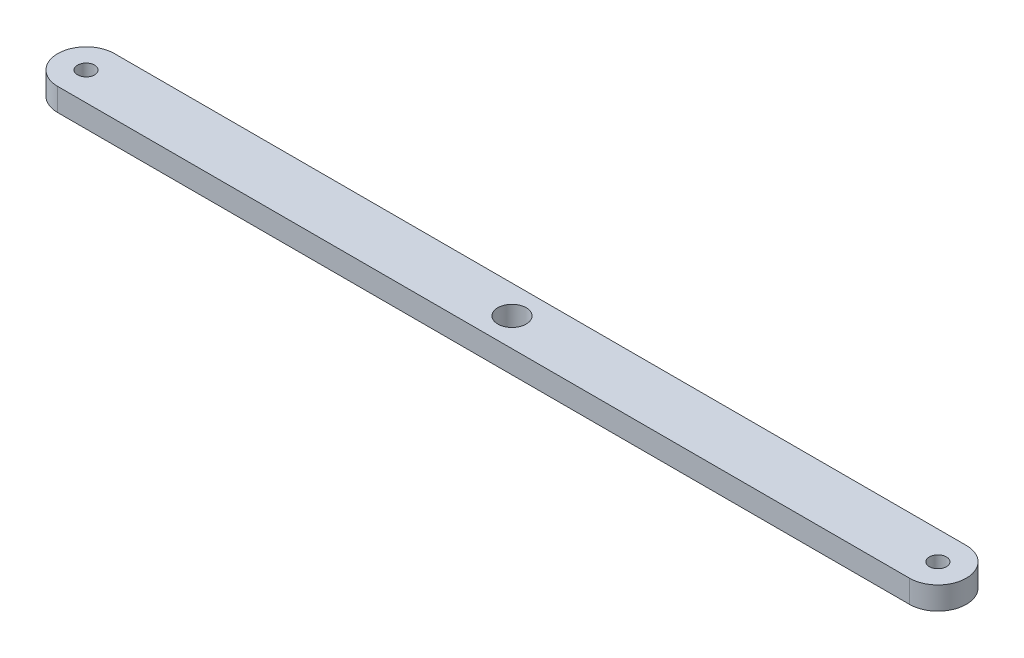
SolidWorks part; units mm, degrees
material "ABS"
ref_plane "Спереди" through (0, 0, 0) normal (0, 0, 1) x (1, 0, 0)
ref_plane "Сверху" through (0, 0, 0) normal (0, 1, 0) x (1, 0, 0)
ref_plane "Справа" through (0, 0, 0) normal (1, 0, 0) x (0, 0, -1)
sketch "Эскиз1" plane through (0, 0, 0) normal (0, 1, 0) x (1, 0, 0)
  line L1 (-75, 5) -> (75, 5)
  line L2 (-75, 5) -> (-75, -5) construction
  line L3 (-75, -5) -> (75, -5)
  line L4 (75, 5) -> (75, -5) construction
  line L5 (-75, 5) -> (75, -5) construction
  line L6 (-75, -5) -> (75, 5) construction
  line L7 (75, 0) -> (-75, 0) construction
  arc A0 (-75, -5) -> (-75, 5) centre (-75, 0) cw
  arc A1 (75, 5) -> (74.3363, -4.9558) centre (75, 0) cw
  circle A2 centre (-75, 0) radius 1.5
  circle A3 centre (75, 0) radius 1.5
  circle A4 centre (0, 0) radius 2.5
  point P0 (0, 0)
  dimension "D1" = 10
  dimension "D2" = 3
  dimension "D3" = 5
  dimension "D4" = 3
  dimension "D5" = 150
extrude "Бобышка-Вытянуть1" add sketch "Эскиз1" along normal blind 4
